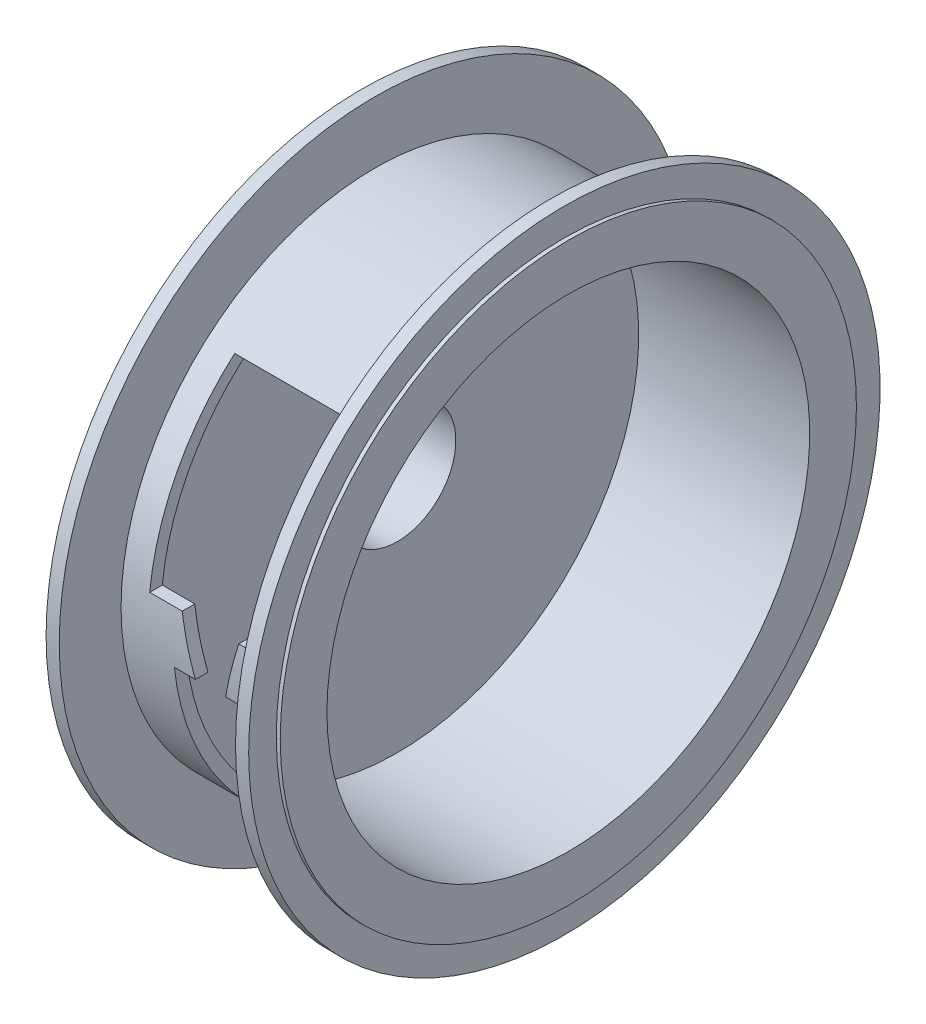
SolidWorks part; units mm, degrees
ref_plane "Ön Düzlem" through (0, 0, 0) normal (0, 0, 1) x (1, 0, 0)
ref_plane "Üst Düzlem" through (0, 0, 0) normal (0, 1, 0) x (1, 0, 0)
ref_plane "Sağ Düzlem" through (0, 0, 0) normal (1, 0, 0) x (0, 0, -1)
sketch "Çizim1" plane through (0, 0, 0) normal (0, 0, 1) x (1, 0, 0)
  line L0 (-5.3665, 0) -> (47.9329, 0) construction
  line L1 (0.3, 18.5) -> (0.3, 21.9)
  line L2 (0.6, 24) -> (1.6, 24)
  line L3 (1.6, 24) -> (1.6, 19.3)
  line L4 (1.6, 19.3) -> (15, 19.3)
  line L5 (15, 19.3) -> (15, 24)
  line L6 (15, 24) -> (16, 24)
  line L7 (16.3, 21.9) -> (16.3, 18.35)
  line L8 (16.3, 18.35) -> (3.3, 18.35)
  line L9 (0.3, 18.5) -> (2, 18.5)
  line L10 (2, 18.5) -> (2, 6.1)
  line L11 (2, 6.1) -> (0, 6.1)
  line L12 (0, 6.1) -> (0, 4.45)
  line L13 (0, 4.45) -> (3.3, 4.45)
  line L14 (3.3, 4.45) -> (3.3, 18.35)
  line L15 (0.3, 21.9) -> (0.6, 21.9)
  line L16 (0.6, 21.9) -> (0.6, 24)
  line L17 (16.3, 21.9) -> (16, 21.9)
  line L18 (16, 21.9) -> (16, 24)
  dimension "D1" = 48
  dimension "D2" = 1.3
  dimension "D3" = 1
  dimension "D4" = 43.8
  dimension "D5" = 37
  dimension "D6" = 12.2
  dimension "D7" = 8.9
  dimension "D8" = 1.7
  dimension "D9" = 13
  dimension "D10" = 1.3
  dimension "D11" = 38.6
  dimension "D12" = 16
  dimension "D13" = 2
  dimension "D14" = 36.7
revolve "Döndür1" add sketch "Çizim1" angle 360 about L0
sketch "Çizim2" plane through (0, 0, 0) normal (0, 0, 1) x (1, 0, 0)
  line L0 (-4.7871, 0) -> (21.5576, 0) construction
  line L1 (8.3, 19.3) -> (8.3, -19.3) construction
  line L2 (15, 19.3) -> (1.6, 19.3) construction
  line L3 (1.6, -19.3) -> (15, -19.3) construction
  line L4 (12.925, 14.5) -> (3.675, 14.5)
  line L5 (3.675, 14.5) -> (3.675, 2)
  line L6 (3.675, 2) -> (6.15, 2)
  line L7 (6.15, 2) -> (7.15, -2)
  line L8 (7.15, -2) -> (5.55, -2)
  line L9 (5.55, -2) -> (5.55, -14.5)
  line L10 (5.55, -14.5) -> (11.05, -14.5)
  line L11 (11.05, -2) -> (11.05, -14.5)
  line L12 (9.45, -2) -> (11.05, -2)
  line L13 (10.45, 2) -> (9.45, -2)
  line L14 (12.925, 2) -> (10.45, 2)
  line L15 (12.925, 14.5) -> (12.925, 2)
  point P18 (8.3, -14.5)
  point P23 (8.3, 14.5)
  dimension "D1" = 9.25
  dimension "D2" = 5.5
  dimension "D3" = 12.5
  dimension "D4" = 14.5
  dimension "D5" = 4.3
  dimension "D6" = 2.3
extrude "Kes-Ekstrüzyon1" cut sketch "Çizim2" along normal through all
